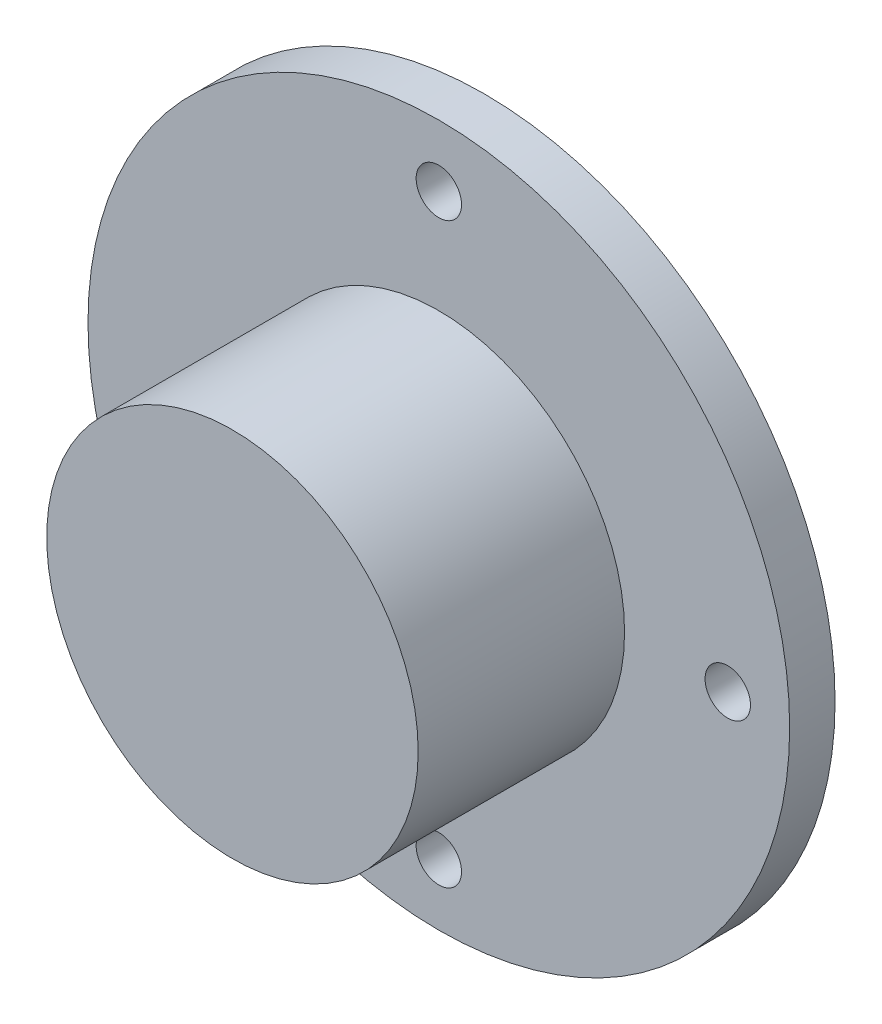
SolidWorks part; units mm, degrees
ref_plane "Front Plane" through (0, 0, 0) normal (0, 0, 1) x (1, 0, 0)
ref_plane "Top Plane" through (0, 0, 0) normal (0, 1, 0) x (1, 0, 0)
ref_plane "Right Plane" through (0, 0, 0) normal (1, 0, 0) x (0, 0, -1)
sketch "Outer_race_keeper_flange_profile" plane through (0, 0, 0) normal (0, 0, 1) x (1, 0, 0)
  circle A0 centre (0, 0) radius 17
  dimension "D1" = 34
extrude "Outer_race_keeper_flange" add sketch "Outer_race_keeper_flange_profile" along normal blind 2
sketch "Housing_contact_rim_preserves_bearing_float_profile" plane through (0, 0, 0) normal (0, 0, 1) x (1, 0, 0)
  circle A0 centre (0, 0) radius 17
  circle A1 centre (0, 0) radius 11.2
  dimension "D1" = 34
  dimension "D2" = 22.4
extrude "Housing_contact_rim_preserves_bearing_float" add sketch "Housing_contact_rim_preserves_bearing_float_profile" along normal blind 0.2 from offset 0.2
sketch "Pin_end_cover_profile" plane through (0, 0, 0) normal (0, 0, 1) x (1, 0, 0)
  circle A0 centre (0, 0) radius 9
  dimension "D1" = 18
extrude "Pin_end_cover" add sketch "Pin_end_cover_profile" along normal blind 12
sketch "Dowel_end_float_pocket_profile" plane through (0, 0, 0) normal (0, 0, 1) x (1, 0, 0)
  circle A0 centre (0, 0) radius 7
  dimension "D1" = 14
extrude "Dowel_end_float_pocket_depth9" cut sketch "Dowel_end_float_pocket_profile" along normal blind 9
sketch "Keeper_M2_fasteners_profile" plane through (0, 0, 0) normal (0, 0, 1) x (1, 0, 0)
  circle A0 centre (14, 0) radius 1.1
  circle A1 centre (0, -14) radius 1.1
  circle A2 centre (0, 14) radius 1.1
  dimension "D1" = 2.2
  dimension "D2" = 2.2
  dimension "D3" = 2.2
extrude "Keeper_M2_fasteners" cut sketch "Keeper_M2_fasteners_profile" along normal through all from offset 50
